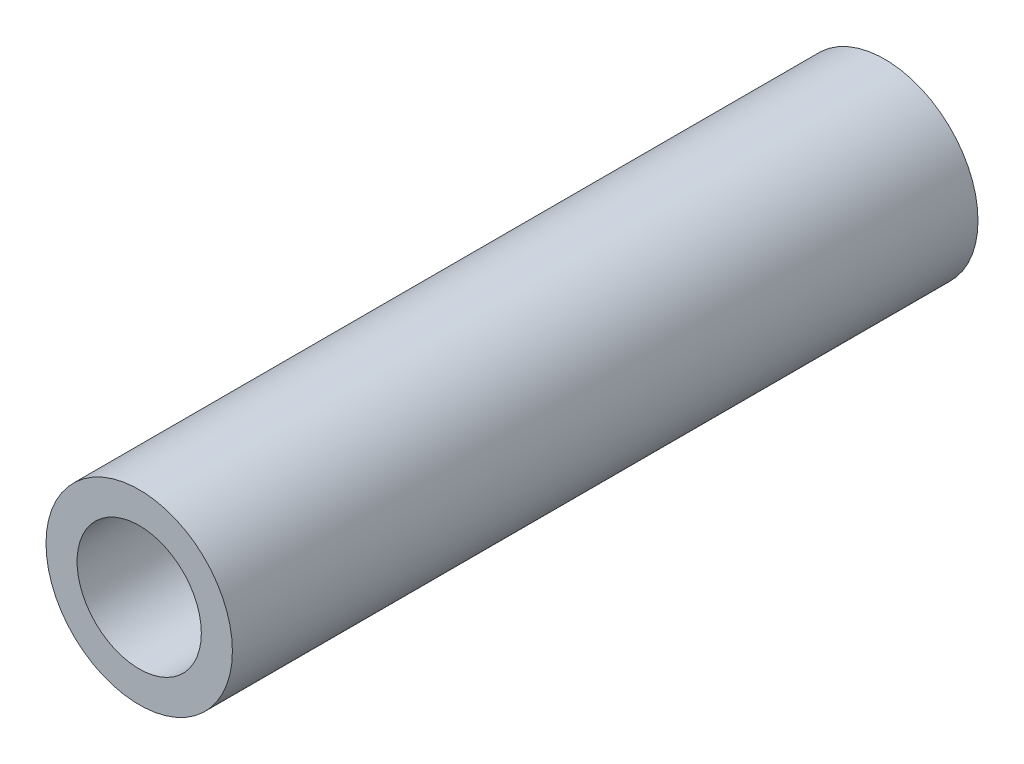
SolidWorks part; units mm, degrees
material "Alliage 1060"
ref_plane "Plan de face" through (0, 0, 0) normal (0, 0, 1) x (1, 0, 0)
ref_plane "Plan de dessus" through (0, 0, 0) normal (0, 1, 0) x (1, 0, 0)
ref_plane "Plan de droite" through (0, 0, 0) normal (1, 0, 0) x (0, 0, -1)
sketch "Esquisse1" plane through (0, 0, 0) normal (0, 0, 1) x (1, 0, 0)
  circle A0 centre (0, 0) radius 2
  circle A1 centre (0, 0) radius 3
  dimension "D1" = 4
  dimension "D2" = 6
extrude "Boss.-Extru.1" add sketch "Esquisse1" along normal blind 24
